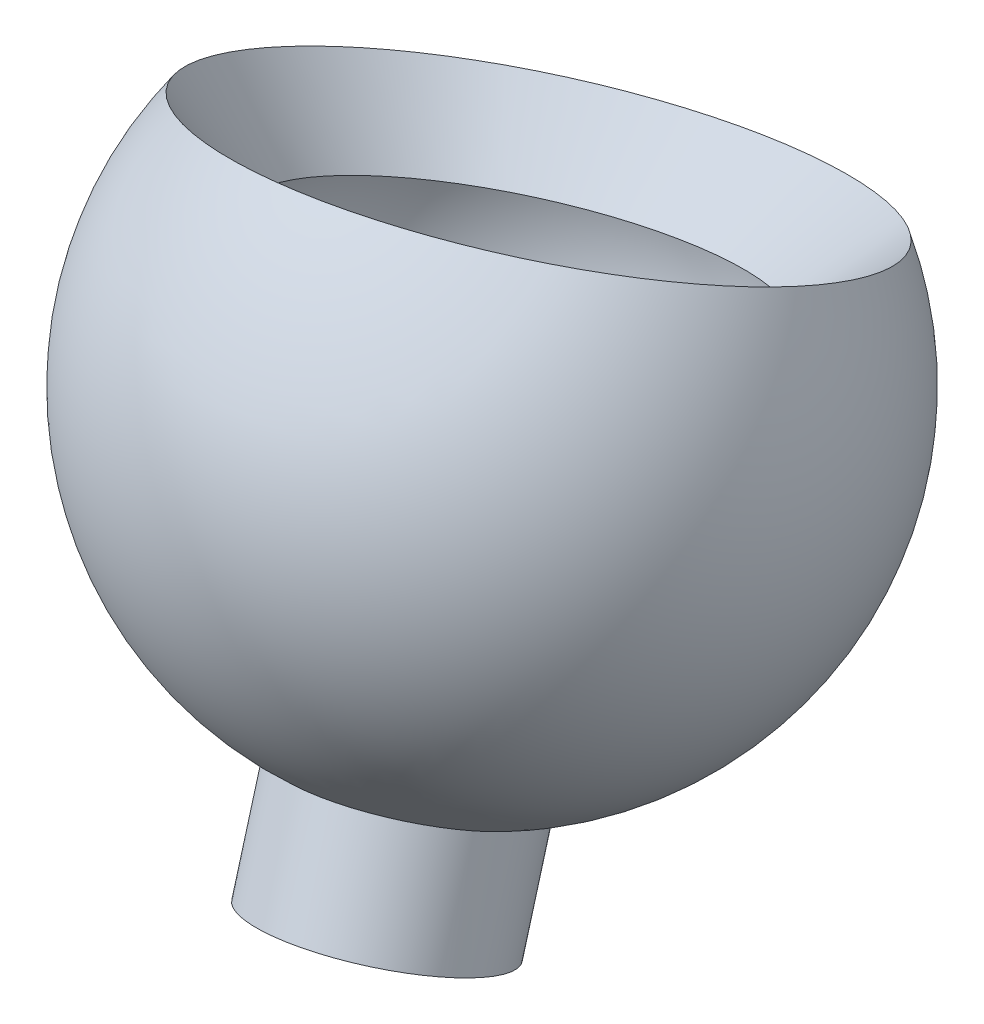
SolidWorks part; units mm, degrees
other "Cable End Ball Socket"
other "Cable End Ball Socket Left"
ref_plane "Front Plane" through (0, 0, 0) normal (0, 0, 1) x (1, 0, 0)
ref_plane "Top Plane" through (0, 0, 0) normal (0, 1, 0) x (1, 0, 0)
ref_plane "Right Plane" through (0, 0, 0) normal (1, 0, 0) x (0, 0, -1)
sketch3d "Turned socket body axis line"
  line L0 (-24.4208, -99.1604, -22.8742) -> (-22.3446, -80.8396, -15.1258) construction
ref_axis "Turned socket body axis" through (-24.4208, -99.1604, -22.8742) along (0.1038, 0.916, 0.3874)
sketch3d "Ball socket turned profile datum points"
  point P0 (-23.3827, -90, -19)
  point P1 (-22.3446, -80.8396, -15.1258)
  point P2 (-13.4367, -90.9561, -19.4044)
ref_plane "Ball socket turned profile plane" through (0, -6.8394, 16.1713) normal (0, 0.3895, -0.921) x (-1, 0, 0)
sketch "Ball socket turned profile" plane through (0, -6.8394, 16.1713) normal (0, 0.3895, -0.921) x (-1, 0, 0)
  line L0 (21.4504, -86.2284) -> (21.2887, -84.6794)
  line L1 (21.2887, -84.6794) -> (22.0346, -84.6016)
  line L2 (22.0346, -84.6016) -> (22.2838, -86.9886)
  line L3 (22.2838, -86.9886) -> (23.0297, -86.9107)
  line L4 (23.0297, -86.9107) -> (23.0609, -87.2091)
  line L5 (20.7241, -91.8867) -> (19.8043, -93.0209)
  arc A0 (21.4504, -86.2284) -> (19.8043, -93.0209) centre (23.3827, -90.2924) ccw
  arc A1 (23.0609, -87.2091) -> (20.7241, -91.8867) centre (23.3827, -90.2924) ccw
revolve "Turned socket body" add sketch "Ball socket turned profile" angle 360 about axis through (-24.4208, -99.1604, -22.8742) along (0.1038, 0.916, 0.3874)
sketch3d "Mirror1 profile datum points"
  point P0 (0, 0, 0)
  point P1 (10, 0, 0)
  point P2 (0, 0, 10)
ref_plane "Mirror1 profile plane" through (0, 0, 0) normal (0, -1, 0) x (-1, 0, 0)
mirror "Mirror1" about plane through (0, 0, 0) normal (0, -1, 0) of bodies 101
delete or keep bodies "Remove1" type delete bodies bodies 101
